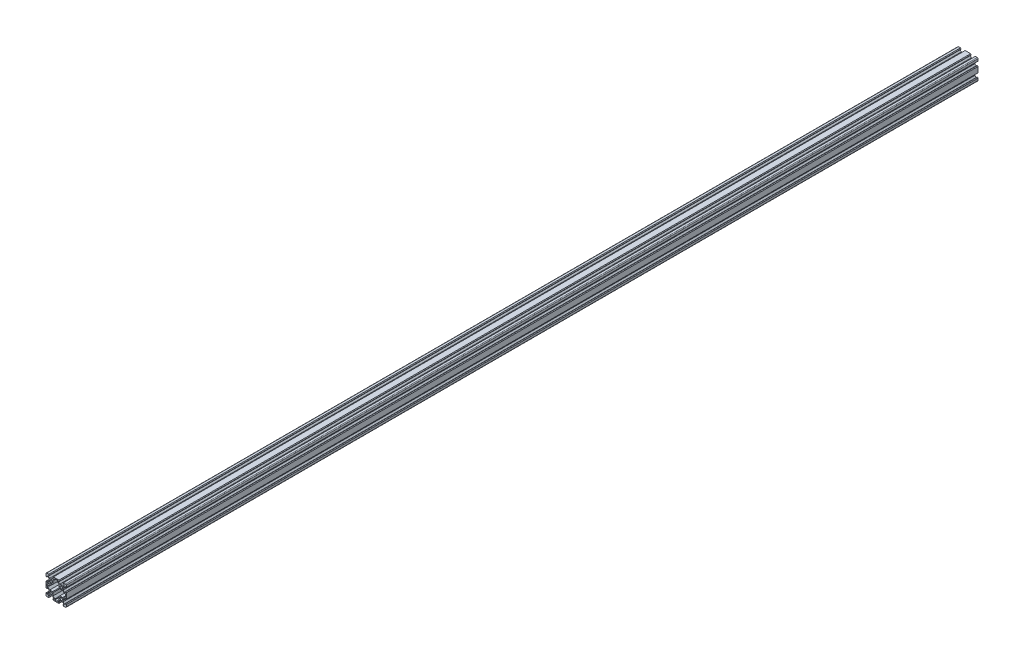
SolidWorks part; units mm, degrees
material "6061-T6 (SS)"
ref_plane "Front Plane" through (0, 0, 0) normal (0, 0, 1) x (1, 0, 0)
ref_plane "Top Plane" through (0, 0, 0) normal (0, 1, 0) x (1, 0, 0)
ref_plane "Right Plane" through (0, 0, 0) normal (1, 0, 0) x (0, 0, -1)
sketch "Sketch1" plane through (0, 0, 0) normal (0, 0, 1) x (1, 0, 0)
  line L1 (18.5, -20) -> (-18.5, -20)
  line L2 (20, -18.5) -> (20, 18.5)
  line L3 (18.5, 20) -> (-18.5, 20)
  line L4 (-20, -18.5) -> (-20, 18.5)
  line L5 (20, -20) -> (-20, 20) construction
  line L6 (20, 20) -> (-20, -20) construction
  circle A0 centre (-10, 10) radius 2.3
  circle A1 centre (10, -10) radius 2.3
  circle A2 centre (10, 10) radius 2.3
  circle A3 centre (-10, -10) radius 2.3
  arc A4 (-18.5, -20) -> (-20, -18.5) centre (-18.5, -18.5) cw
  arc A5 (18.5, -20) -> (20, -18.5) centre (18.5, -18.5) ccw
  arc A6 (20, 18.5) -> (18.5, 20) centre (18.5, 18.5) ccw
  arc A7 (-18.5, 20) -> (-20, 18.5) centre (-18.5, 18.5) ccw
  point P0 (0, 0)
  line B0 (-10, 10) -> (-10, 20) construction
  line B1 (-10, 13.69) -> (-10.21, 13.9)
  line B2 (-10.21, 13.9) -> (-12.8393, 13.9)
  line B3 (-12.8393, 13.9) -> (-15.5, 16.5607)
  line B4 (-15.5, 16.5607) -> (-15.5, 18.2)
  line B5 (-15.5, 18.2) -> (-13.395, 18.2)
  line B6 (-13.395, 18.2) -> (-13.395, 18.815)
  line B7 (-13.395, 18.815) -> (-14.58, 20)
  line B8 (-14.58, 20) -> (-5.42, 20)
  line B9 (-10, 10) -> (-15.9132, 15.9132) construction
  line B10 (-6.605, 18.815) -> (-5.42, 20)
  line B11 (-6.605, 18.2) -> (-6.605, 18.815)
  line B12 (-4.5, 18.2) -> (-6.605, 18.2)
  line B13 (-4.5, 16.5607) -> (-4.5, 18.2)
  line B14 (-7.1607, 13.9) -> (-4.5, 16.5607)
  line B15 (-9.79, 13.9) -> (-7.1607, 13.9)
  line B16 (-10, 13.69) -> (-9.79, 13.9)
  line B17 (10, 10) -> (10, 20) construction
  line B18 (10, 13.69) -> (9.79, 13.9)
  line B19 (9.79, 13.9) -> (7.1607, 13.9)
  line B20 (7.1607, 13.9) -> (4.5, 16.5607)
  line B21 (4.5, 16.5607) -> (4.5, 18.2)
  line B22 (4.5, 18.2) -> (6.605, 18.2)
  line B23 (6.605, 18.2) -> (6.605, 18.815)
  line B24 (6.605, 18.815) -> (5.42, 20)
  line B25 (5.42, 20) -> (14.58, 20)
  line B26 (10, 10) -> (4.0868, 15.9132) construction
  line B27 (13.395, 18.815) -> (14.58, 20)
  line B28 (13.395, 18.2) -> (13.395, 18.815)
  line B29 (15.5, 18.2) -> (13.395, 18.2)
  line B30 (15.5, 16.5607) -> (15.5, 18.2)
  line B31 (12.8393, 13.9) -> (15.5, 16.5607)
  line B32 (10.21, 13.9) -> (12.8393, 13.9)
  line B33 (10, 13.69) -> (10.21, 13.9)
  line B34 (-10, 10) -> (-20, 10) construction
  line B35 (-13.69, 10) -> (-13.9, 9.79)
  line B36 (-13.9, 9.79) -> (-13.9, 7.1607)
  line B37 (-13.9, 7.1607) -> (-16.5607, 4.5)
  line B38 (-16.5607, 4.5) -> (-18.2, 4.5)
  line B39 (-18.2, 4.5) -> (-18.2, 6.605)
  line B40 (-18.2, 6.605) -> (-18.815, 6.605)
  line B41 (-18.815, 6.605) -> (-20, 5.42)
  line B42 (-20, 5.42) -> (-20, 14.58)
  line B43 (-10, 10) -> (-15.9132, 4.0868) construction
  line B44 (-18.815, 13.395) -> (-20, 14.58)
  line B45 (-18.2, 13.395) -> (-18.815, 13.395)
  line B46 (-18.2, 15.5) -> (-18.2, 13.395)
  line B47 (-16.5607, 15.5) -> (-18.2, 15.5)
  line B48 (-13.9, 12.8393) -> (-16.5607, 15.5)
  line B49 (-13.9, 10.21) -> (-13.9, 12.8393)
  line B50 (-13.69, 10) -> (-13.9, 10.21)
  line B51 (-10, -10) -> (-20, -10) construction
  line B52 (-13.69, -10) -> (-13.9, -10.21)
  line B53 (-13.9, -10.21) -> (-13.9, -12.8393)
  line B54 (-13.9, -12.8393) -> (-16.5607, -15.5)
  line B55 (-16.5607, -15.5) -> (-18.2, -15.5)
  line B56 (-18.2, -15.5) -> (-18.2, -13.395)
  line B57 (-18.2, -13.395) -> (-18.815, -13.395)
  line B58 (-18.815, -13.395) -> (-20, -14.58)
  line B59 (-20, -14.58) -> (-20, -5.42)
  line B60 (-10, -10) -> (-15.9132, -15.9132) construction
  line B61 (-18.815, -6.605) -> (-20, -5.42)
  line B62 (-18.2, -6.605) -> (-18.815, -6.605)
  line B63 (-18.2, -4.5) -> (-18.2, -6.605)
  line B64 (-16.5607, -4.5) -> (-18.2, -4.5)
  line B65 (-13.9, -7.1607) -> (-16.5607, -4.5)
  line B66 (-13.9, -9.79) -> (-13.9, -7.1607)
  line B67 (-13.69, -10) -> (-13.9, -9.79)
  line B68 (-10, -10) -> (-10, -20) construction
  line B69 (-10, -13.69) -> (-9.79, -13.9)
  line B70 (-9.79, -13.9) -> (-7.1607, -13.9)
  line B71 (-7.1607, -13.9) -> (-4.5, -16.5607)
  line B72 (-4.5, -16.5607) -> (-4.5, -18.2)
  line B73 (-4.5, -18.2) -> (-6.605, -18.2)
  line B74 (-6.605, -18.2) -> (-6.605, -18.815)
  line B75 (-6.605, -18.815) -> (-5.42, -20)
  line B76 (-5.42, -20) -> (-14.58, -20)
  line B77 (-10, -10) -> (-4.0868, -15.9132) construction
  line B78 (-13.395, -18.815) -> (-14.58, -20)
  line B79 (-13.395, -18.2) -> (-13.395, -18.815)
  line B80 (-15.5, -18.2) -> (-13.395, -18.2)
  line B81 (-15.5, -16.5607) -> (-15.5, -18.2)
  line B82 (-12.8393, -13.9) -> (-15.5, -16.5607)
  line B83 (-10.21, -13.9) -> (-12.8393, -13.9)
  line B84 (-10, -13.69) -> (-10.21, -13.9)
  line B85 (10, -10) -> (10, -20) construction
  line B86 (10, -13.69) -> (10.21, -13.9)
  line B87 (10.21, -13.9) -> (12.8393, -13.9)
  line B88 (12.8393, -13.9) -> (15.5, -16.5607)
  line B89 (15.5, -16.5607) -> (15.5, -18.2)
  line B90 (15.5, -18.2) -> (13.395, -18.2)
  line B91 (13.395, -18.2) -> (13.395, -18.815)
  line B92 (13.395, -18.815) -> (14.58, -20)
  line B93 (14.58, -20) -> (5.42, -20)
  line B94 (10, -10) -> (15.9132, -15.9132) construction
  line B95 (6.605, -18.815) -> (5.42, -20)
  line B96 (6.605, -18.2) -> (6.605, -18.815)
  line B97 (4.5, -18.2) -> (6.605, -18.2)
  line B98 (4.5, -16.5607) -> (4.5, -18.2)
  line B99 (7.1607, -13.9) -> (4.5, -16.5607)
  line B100 (9.79, -13.9) -> (7.1607, -13.9)
  line B101 (10, -13.69) -> (9.79, -13.9)
  line B102 (10, 10) -> (20, 10) construction
  line B103 (13.69, 10) -> (13.9, 10.21)
  line B104 (13.9, 10.21) -> (13.9, 12.8393)
  line B105 (13.9, 12.8393) -> (16.5607, 15.5)
  line B106 (16.5607, 15.5) -> (18.2, 15.5)
  line B107 (18.2, 15.5) -> (18.2, 13.395)
  line B108 (18.2, 13.395) -> (18.815, 13.395)
  line B109 (18.815, 13.395) -> (20, 14.58)
  line B110 (20, 14.58) -> (20, 5.42)
  line B111 (10, 10) -> (15.9132, 15.9132) construction
  line B112 (18.815, 6.605) -> (20, 5.42)
  line B113 (18.2, 6.605) -> (18.815, 6.605)
  line B114 (18.2, 4.5) -> (18.2, 6.605)
  line B115 (16.5607, 4.5) -> (18.2, 4.5)
  line B116 (13.9, 7.1607) -> (16.5607, 4.5)
  line B117 (13.9, 9.79) -> (13.9, 7.1607)
  line B118 (13.69, 10) -> (13.9, 9.79)
  line B119 (10, -10) -> (20, -10) construction
  line B120 (13.69, -10) -> (13.9, -9.79)
  line B121 (13.9, -9.79) -> (13.9, -7.1607)
  line B122 (13.9, -7.1607) -> (16.5607, -4.5)
  line B123 (16.5607, -4.5) -> (18.2, -4.5)
  line B124 (18.2, -4.5) -> (18.2, -6.605)
  line B125 (18.2, -6.605) -> (18.815, -6.605)
  line B126 (18.815, -6.605) -> (20, -5.42)
  line B127 (20, -5.42) -> (20, -14.58)
  line B128 (10, -10) -> (15.9132, -4.0868) construction
  line B129 (18.815, -13.395) -> (20, -14.58)
  line B130 (18.2, -13.395) -> (18.815, -13.395)
  line B131 (18.2, -15.5) -> (18.2, -13.395)
  line B132 (16.5607, -15.5) -> (18.2, -15.5)
  line B133 (13.9, -12.8393) -> (16.5607, -15.5)
  line B134 (13.9, -10.21) -> (13.9, -12.8393)
  line B135 (13.69, -10) -> (13.9, -10.21)
  line B136 (-18.2, -2.7) -> (-18.2, 2.7)
  line B137 (-18.2, 2.7) -> (-16.2393, 2.7)
  line B138 (-16.2393, 2.7) -> (-12.8393, 6.1)
  line B139 (-12.8393, 6.1) -> (-7.1607, 6.1)
  line B140 (-10, 6.1) -> (-10, 0) construction
  line B141 (-10, 0) -> (-18.2, 0) construction
  line B142 (-12.8393, -6.1) -> (-7.1607, -6.1)
  line B143 (-16.2393, -2.7) -> (-12.8393, -6.1)
  line B144 (-18.2, -2.7) -> (-16.2393, -2.7)
  line B145 (-10, 6.1) -> (-10, 10) construction
  line B146 (-10, 10) -> (-15.0927, 4.9073) construction
  line B147 (-10, 10) -> (-6.3747, 6.3747) construction
  line B148 (2.7, 18.2) -> (2.7, 16.2393)
  line B149 (2.7, 16.2393) -> (6.1, 12.8393)
  line B150 (6.1, 12.8393) -> (6.1, 7.1607)
  line B151 (-6.1, 12.8393) -> (-6.1, 7.1607)
  line B152 (-2.7, 16.2393) -> (-6.1, 12.8393)
  line B153 (-2.7, 18.2) -> (-2.7, 16.2393)
  line B154 (2.7, 18.2) -> (-2.7, 18.2)
  line B155 (2.7, -18.2) -> (-2.7, -18.2)
  line B156 (-2.7, -18.2) -> (-2.7, -16.2393)
  line B157 (-2.7, -16.2393) -> (-6.1, -12.8393)
  line B158 (-6.1, -12.8393) -> (-6.1, -7.1607)
  line B159 (6.1, -12.8393) -> (6.1, -7.1607)
  line B160 (2.7, -16.2393) -> (6.1, -12.8393)
  line B161 (2.7, -18.2) -> (2.7, -16.2393)
  line B162 (0, 18.2) -> (0, -18.2) construction
  line B163 (12.8393, -6.1) -> (7.1607, -6.1)
  line B164 (16.2393, -2.7) -> (12.8393, -6.1)
  line B165 (18.2, -2.7) -> (16.2393, -2.7)
  line B166 (18.2, -2.7) -> (18.2, 2.7)
  line B167 (18.2, 2.7) -> (16.2393, 2.7)
  line B168 (16.2393, 2.7) -> (12.8393, 6.1)
  line B169 (12.8393, 6.1) -> (7.1607, 6.1)
  line B170 (-7.1607, 6.1) -> (-6.1, 7.1607)
  line B171 (6.1, 7.1607) -> (7.1607, 6.1)
  line B172 (7.1607, -6.1) -> (6.1, -7.1607)
  line B173 (-6.1, -7.1607) -> (-7.1607, -6.1)
  dimension "D4" = 4.6
  dimension "D5" = 1.5
  dimension "D1" = 40
  dimension "D2" = 10
  dimension "D3" = 10
sketch_block_instance "V Slot 2-1"
sketch_block "V Slot 2" parameters "D1"=10, "D2"=11, "D3"=4.3, "D4"=1.8, "D5"=0.21, "D6"=45, "D7"=9.16, "D8"=1.5, "D9"=6.79
sketch_block_instance "V Slot 2-2"
sketch_block_instance "V Slot 2-3"
sketch_block_instance "V Slot 2-4"
sketch_block_instance "V Slot 2-5"
sketch_block_instance "V Slot 2-6"
sketch_block_instance "V Slot 2-7"
sketch_block_instance "V Slot 2-8"
sketch_block_instance "Center Cutout 2-1"
sketch_block "Center Cutout 2" parameters "D1"=5.4, "D2"=12.2, "D3"=8.2, "D4"=45, "D5"=10, "D6"=1.5
extrude "Boss-Extrude1" add sketch "Sketch1" along normal blind 1800 contours B135 B120 B121 B122 B123 B124 B125 B126 L2 B112 B113 B114 B115 B116 B117 B118 B103 B104 B105 B106 B107 B108 B109 A6 L3 B27 B28 B29 B30 B31 B32 B33 B18 B19 B20 B21 B22 B23 B24 B10 B11 B12 B13 B14 B15 B16 B1 B2 B3
